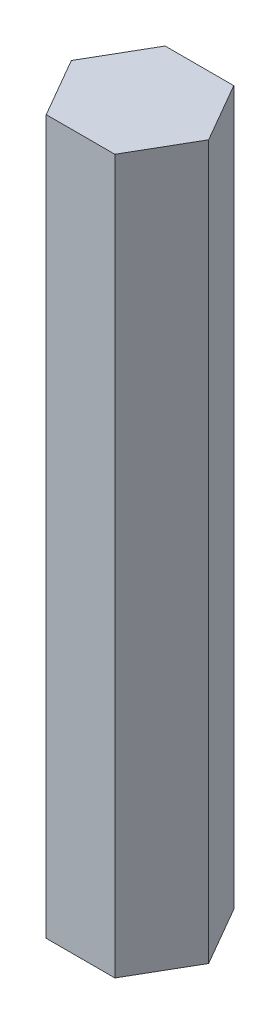
SolidWorks part; units mm, degrees
material "AISI 304"
ref_plane "Front Plane" through (0, 0, 0) normal (0, 0, 1) x (1, 0, 0)
ref_plane "Top Plane" through (0, 0, 0) normal (0, 1, 0) x (1, 0, 0)
ref_plane "Right Plane" through (0, 0, 0) normal (1, 0, 0) x (0, 0, -1)
sketch "Sketch1" plane through (0, 0, 0) normal (0, 1, 0) x (1, 0, 0)
  line L1 (2.8868, 0) -> (1.4434, 2.5)
  line L2 (1.4434, 2.5) -> (-1.4434, 2.5)
  line L3 (-1.4434, 2.5) -> (-2.8868, 0)
  line L4 (-2.8868, 0) -> (-1.4434, -2.5)
  line L5 (-1.4434, -2.5) -> (1.4434, -2.5)
  line L6 (1.4434, -2.5) -> (2.8868, 0)
  circle A0 centre (0, 0) radius 2.5 construction
  dimension "D1" = 5
extrude "Boss-Extrude1" add sketch "Sketch1" along normal blind 30
